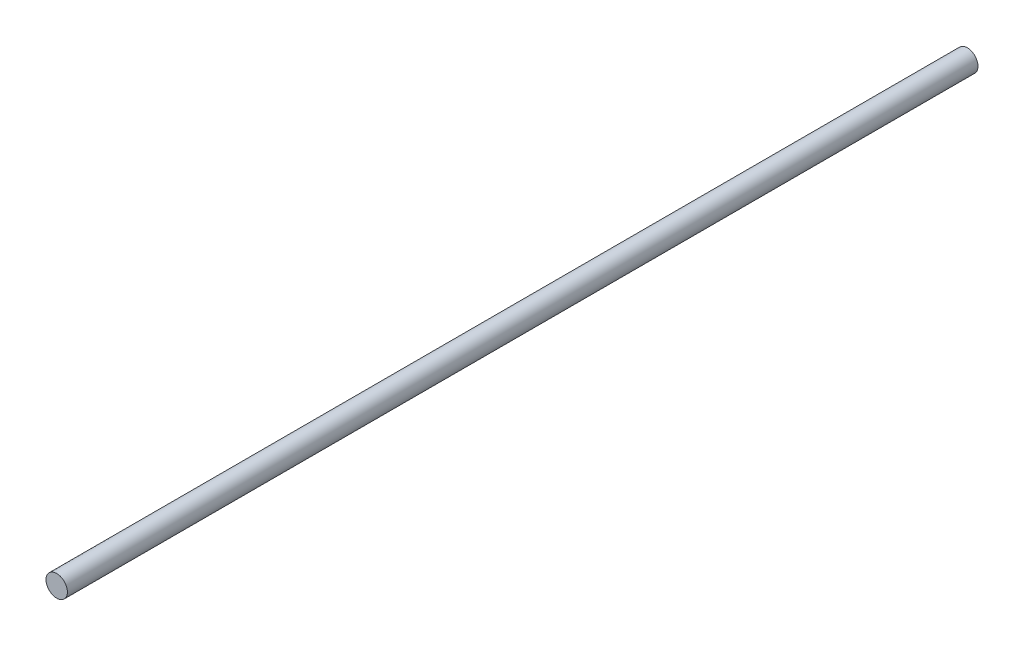
SolidWorks part; units mm, degrees
material "1023 Carbon Steel Sheet (SS)"
ref_plane "Front Plane" through (0, 0, 0) normal (1, 0, 0) x (0, 1, 0)
ref_plane "Top Plane" through (0, 0, 0) normal (0, 0, 1) x (0, 1, 0)
ref_plane "Right Plane" through (0, 0, 0) normal (0, 1, 0) x (-1, 0, 0)
sketch "Sketch1" plane through (0, 0, 0) normal (0, 0, 1) x (0, 1, 0)
  circle A0 centre (0, 0) radius 4
  dimension "D1" = 8
extrude "Boss-Extrude1" add sketch "Sketch1" along normal blind 340 contours A0
